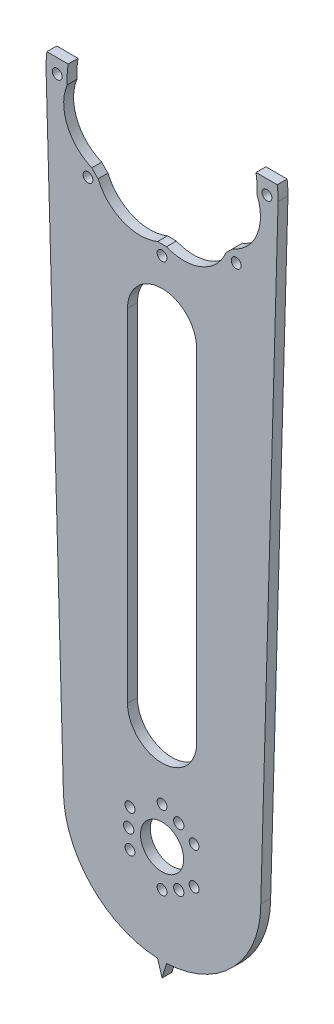
SolidWorks part; units mm, degrees
ref_plane "前视基准面" through (0, 0, 0) normal (0, 0, 1) x (1, 0, 0)
ref_plane "上视基准面" through (0, 0, 0) normal (0, 1, 0) x (1, 0, 0)
ref_plane "右视基准面" through (0, 0, 0) normal (1, 0, 0) x (0, 0, -1)
sketch "草图3" plane through (0, 0, 0) normal (0, 0, 1) x (1, 0, 0)
  line L0 (0, 53.0098) -> (0, -196.9902) construction
  line L7 (0, -196.9902) -> (0, -200.34) construction
  line L11 (0, -153.5642) -> (0, -15.006) construction
  line L12 (-14, -153.5642) -> (-14, -15.006)
  line L13 (14, -153.5642) -> (14, -15.006)
  line L98 (-38.071, 58.7409) -> (-46.6734, 58.7409)
  line L110 (0, -236.9902) -> (0, -242.9902) construction
  line L111 (0, -242.9902) -> (-1.8118, -236.9492)
  line L114 (0, -242.9902) -> (1.8118, -236.9492)
  line L116 (-47.0239, 53.0098) -> (-40, -196.9902)
  line L117 (38.071, 58.7409) -> (46.6734, 58.7409)
  line L118 (47.0239, 53.0098) -> (40, -196.9902)
  line L119 (-1.8118, 14.5524) -> (1.8118, 14.5524)
  circle A4 centre (0, 10.5098) radius 2
  circle A5 centre (-30.052, 22.9577) radius 2
  circle A6 centre (-42.5, 53.0098) radius 2
  circle A11 centre (30.052, 22.9577) radius 2
  arc A12 (-38.071, 58.7409) -> (34.5093, 35.9406) centre (0, 53.0098) ccw construction
  circle A13 centre (42.5, 53.0098) radius 2 [skipped]
  circle A14 centre (30.052, 83.0618) radius 2 [skipped]
  circle A15 centre (-30.052, 83.0618) radius 2 [skipped]
  circle A16 centre (0, 95.5098) radius 2 [skipped]
  arc A30 (-38.4574, 51.2) -> (-28.4746, 27.0974) centre (-21.4147, 44.1402) ccw
  arc A31 (-25.9138, 24.5366) -> (-28.4746, 27.0974) centre (0, 53.0098) cw
  arc A32 (-38.4574, 51.2) -> (-38.071, 58.7409) centre (0, 53.0098) cw
  arc A37 (-25.9138, 24.5366) -> (-1.8118, 14.5524) centre (-8.8707, 31.5955) ccw
  arc A38 (-1.8098, 91.4672) -> (-25.9123, 81.4843) centre (-8.8696, 74.4245) ccw [skipped]
  arc A39 (25.9138, 81.483) -> (1.8118, 91.4671) centre (8.8707, 74.424) ccw [skipped]
  arc A40 (38.4574, 54.8195) -> (28.4746, 78.9221) centre (21.4147, 61.8794) ccw [skipped]
  arc A41 (-28.4732, 78.9236) -> (-38.4573, 54.8215) centre (-21.4143, 61.8805) ccw [skipped]
  arc A42 (28.4732, 27.096) -> (38.4573, 51.198) centre (21.4143, 44.1391) ccw [skipped]
  circle A44 centre (0, 53.0098) radius 47.0239 construction
  circle A48 centre (0, -196.9902) radius 15 construction
  circle A49 centre (0, -196.9902) radius 13.53 construction
  circle A50 centre (0, -211.9902) radius 2
  circle A51 centre (-12.9904, -204.4902) radius 2
  circle A52 centre (-12.9904, -189.4902) radius 2
  circle A53 centre (0, -181.9902) radius 2
  circle A54 centre (12.9904, -189.4902) radius 2
  circle A55 centre (12.9904, -204.4902) radius 2
  circle A56 centre (-13.53, -196.9902) radius 2.08
  circle A57 centre (6.765, -185.2729) radius 2.08
  circle A58 centre (6.765, -208.7075) radius 2.08
  circle A59 centre (0, -196.9902) radius 8.75
  arc A62 (-14, -153.5642) -> (14, -153.5642) centre (0, -153.5642) ccw
  arc A63 (14, -15.006) -> (-14, -15.006) centre (0, -15.006) ccw
  arc A67 (-40, -196.9902) -> (-1.8118, -236.9492) centre (0, -196.9902) ccw
  arc A70 (1.8118, -236.9492) -> (40, -196.9902) centre (0, -196.9902) ccw
  arc A71 (1.8098, 14.5523) -> (25.9123, 24.5352) centre (8.8696, 31.5951) ccw [skipped]
  arc A72 (25.9138, 24.5366) -> (28.4746, 27.0974) centre (0, 53.0098) ccw
  arc A73 (38.4574, 51.2) -> (38.071, 58.7409) centre (0, 53.0098) ccw
  arc A74 (38.4574, 51.2) -> (28.4746, 27.0974) centre (21.4147, 44.1402) cw
  arc A75 (25.9138, 24.5366) -> (1.8118, 14.5524) centre (8.8707, 31.5955) cw
  arc A76 (-46.6734, 58.7409) -> (-47.0239, 53.0098) centre (0, 53.0098) ccw
  arc A77 (46.6734, 58.7409) -> (47.0239, 53.0098) centre (0, 53.0098) cw
  circle A78 centre (42.5, 53.0098) radius 2
  point P31 (0, -84.2851)
  dimension "D1" = 8
  dimension "D2" = 8
extrude "凸台-拉伸1" add sketch "草图3" along normal blind 4
sketch "草图4" plane through (0, 0, 4) normal (0, 0, 1) x (1, 0, 0)
  circle A0 centre (0, -196.9902) radius 5
sketch "草图5" plane through (0, 0, 0) normal (0, 0, -1) x (-1, 0, 0)
  circle A0 centre (0, -197.3859) radius 5
